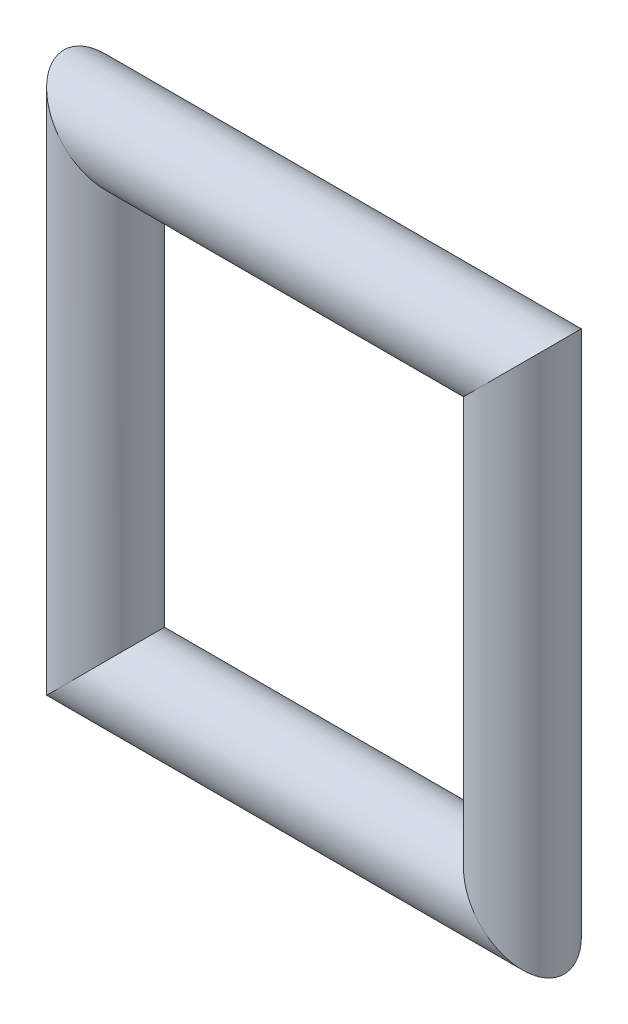
SolidWorks part; units mm, degrees
ref_plane "Front Plane" through (0, 0, 0) normal (0, 0, 1) x (1, 0, 0)
ref_plane "Top Plane" through (0, 0, 0) normal (0, 1, 0) x (1, 0, 0)
ref_plane "Right Plane" through (0, 0, 0) normal (1, 0, 0) x (0, 0, -1)
sketch "Sketch1" plane through (0, 0, 0) normal (0, 0, 1) x (1, 0, 0)
  line L1 (-12.5, -14) -> (12.5, -14)
  line L2 (-12.5, -14) -> (-12.5, 14)
  line L3 (-12.5, 14) -> (12.5, 14)
  line L4 (12.5, -14) -> (12.5, 14)
  line L5 (-12.5, -14) -> (12.5, 14) construction
  line L6 (-12.5, 14) -> (12.5, -14) construction
  point P0 (0, 0)
sweep "Sweep1" add path "Sketch1" circular profile diameter 5 parameters "D3"=5
